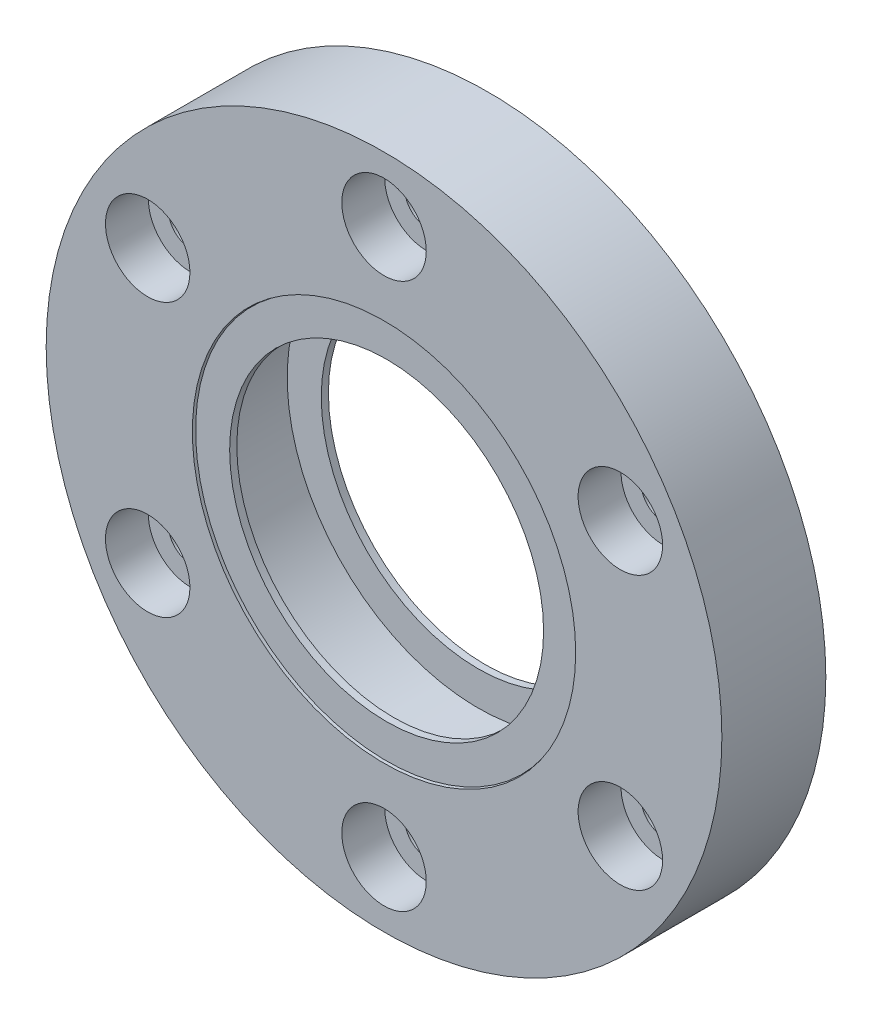
SolidWorks part; units mm, degrees
ref_plane "前视基准面" through (0, 0, 0) normal (0, 0, 1) x (1, 0, 0)
ref_plane "上视基准面" through (0, 0, 0) normal (0, 1, 0) x (1, 0, 0)
ref_plane "右视基准面" through (0, 0, 0) normal (1, 0, 0) x (0, 0, -1)
other "Configuration Table"
sketch "外圈_D52_轴肩D29.5_厚8_截面" plane through (0, 0, 0) normal (0, 0, 1) x (1, 0, 0)
  circle A0 centre (0, 0) radius 26
  circle A1 centre (0, 0) radius 14.75
extrude "外圈_D52_轴肩D29.5_厚8" add sketch "外圈_D52_轴肩D29.5_厚8_截面" along normal blind 8 separate body
sketch "内圈_D10_轴肩D24_厚8_截面" plane through (0, 0, 0) normal (0, 0, 1) x (1, 0, 0)
  circle A0 centre (0, 0) radius 12
  circle A1 centre (0, 0) radius 5
extrude "内圈_D10_轴肩D24_厚8" add sketch "内圈_D10_轴肩D24_厚8_截面" along normal blind 8 separate body
sketch "外圈孔位_PCD42_六等分" plane through (0, 0, 8) normal (0, 0, 1) x (1, 0, 0)
  point P0 (0, 21)
  point P1 (-18.1865, 10.5)
  point P2 (-18.1865, -10.5)
  point P3 (0, -21)
  point P4 (18.1865, -10.5)
  point P5 (18.1865, 10.5)
hole_wizard "外圈_6xD3.4通孔_D6.5沉孔深3.3_PCD42" positions "3D草图1" profile "草图4" counterbore size "M3" standard "ISO" end condition through all
sketch3d "3D草图1"
  point P0 (18.1865, 10.5, 8)
  point P2 (18.1865, -10.5, 8)
  point P4 (0, -21, 8)
  point P6 (-18.1865, -10.5, 8)
  point P8 (-18.1865, 10.5, 8)
  point P10 (0, 21, 8)
sketch "草图4" plane through (18.1865, 10.5, 8) normal (1, 0, 0) x (0, -1, 0)
  line L0 (0, 0) -> (0, 8)
  line L1 (0, 8) -> (1.7, 8)
  line L3 (1.7, 8) -> (1.7, 3.3)
  line L4 (1.7, 3.3) -> (3.25, 3.3)
  line L5 (3.25, 3.3) -> (3.25, 0)
  line L7 (3.25, 0) -> (0, 0)
  line L11 (0, -6.35) -> (0, 107.95) construction
  dimension "通孔孔直径" = 3.4
  dimension "通孔孔深度" = 8
  dimension "柱形沉头孔直径" = 6.5
  dimension "柱形沉头孔深度" = 3.3
sketch "内圈孔位_PCD16_四等分" plane through (0, 0, 8) normal (0, 0, 1) x (1, 0, 0)
  point P0 (5.6569, 5.6569)
  point P1 (-5.6569, 5.6569)
  point P2 (-5.6569, -5.6569)
  point P3 (5.6569, -5.6569)
hole_wizard "内圈_4xM3x0.5通螺纹_PCD16" positions "3D草图2" profile "草图6" tap size "M3" standard "ISO" end condition through all
sketch3d "3D草图2"
  point P0 (5.6569, -5.6569, 8)
  point P2 (-5.6569, -5.6569, 8)
  point P4 (-5.6569, 5.6569, 8)
  point P6 (5.6569, 5.6569, 8)
sketch "草图6" plane through (5.6569, -5.6569, 8) normal (1, 0, 0) x (0, -1, 0)
  line L0 (0, 0) -> (0, 8)
  line L1 (0, 8) -> (1.25, 8)
  line L2 (1.25, 8) -> (1.25, 0)
  line L5 (1.25, 0) -> (0, 0)
  line L11 (0, -6.35) -> (0, 107.95) construction
  dimension "通孔螺纹孔钻头直径" = 2.5
  dimension "通孔螺纹孔钻头深度" = 8
cosmetic thread "孔螺纹线1" parameters "D2"=3
cosmetic thread "孔螺纹线2" parameters "D2"=3
cosmetic thread "孔螺纹线3" parameters "D2"=3
cosmetic thread "孔螺纹线4" parameters "D2"=3
sketch "正面密封圈_示意_截面" plane through (0, 0, 0) normal (0, 0, 1) x (1, 0, 0)
  circle A0 centre (0, 0) radius 14.7
  circle A1 centre (0, 0) radius 12.08
extrude "正面密封圈_示意" add sketch "正面密封圈_示意_截面" along normal blind 0.55 from offset 7.25 separate body
sketch "背面密封圈_示意_截面" plane through (0, 0, 0) normal (0, 0, 1) x (1, 0, 0)
  circle A0 centre (0, 0) radius 14.7
  circle A1 centre (0, 0) radius 12.08
extrude "背面密封圈_示意" add sketch "背面密封圈_示意_截面" along normal blind 0.55 from offset 0.2 separate body
delete or keep bodies "保留外圈与密封圈" type delete bodies bodies 109
